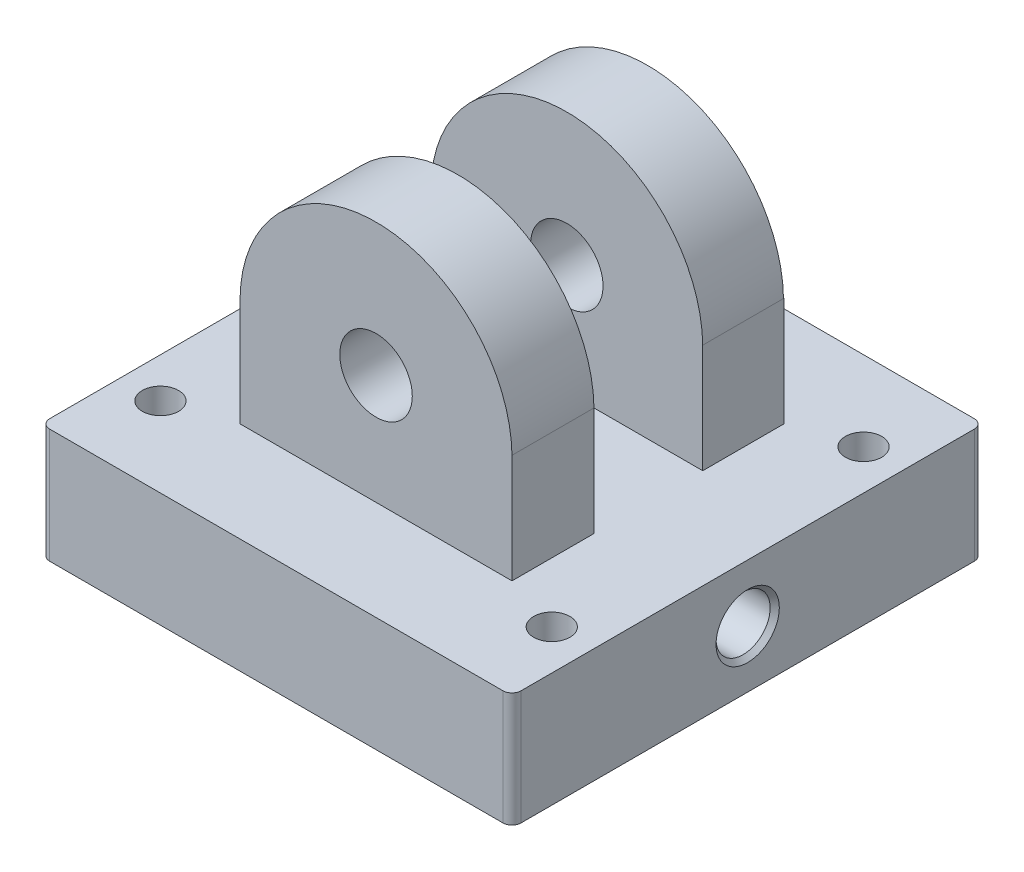
SolidWorks part; units mm, degrees
ref_plane "Front Plane" through (0, 0, 0) normal (0, 0, 1) x (1, 0, 0)
ref_plane "Top Plane" through (0, 0, 0) normal (0, 1, 0) x (1, 0, 0)
ref_plane "Right Plane" through (0, 0, 0) normal (1, 0, 0) x (0, 0, -1)
sketch "Sketch1" plane through (0, 0, 0) normal (0, 1, 0) x (1, 0, 0)
  line L1 (-82.55, 82.55) -> (82.55, 82.55)
  line L2 (-82.55, 82.55) -> (-82.55, -82.55)
  line L3 (-82.55, -82.55) -> (82.55, -82.55)
  line L4 (82.55, 82.55) -> (82.55, -82.55)
  line L5 (-82.55, 82.55) -> (82.55, -82.55) construction
  line L6 (-82.55, -82.55) -> (82.55, 82.55) construction
  point P0 (0, 0)
  dimension "D1" = 165.1
  dimension "D2" = 165.1
extrude "Boss-Extrude1" add sketch "Sketch1" along normal blind 38.1 and the other way blind 2
sketch "Sketch2" plane through (0, 38.1, 0) normal (0, 1, 0) x (1, 0, 0)
  line L1 (-47.625, 47.625) -> (47.625, 47.625)
  line L2 (-47.625, 47.625) -> (-47.625, -47.625)
  line L3 (-47.625, -47.625) -> (47.625, -47.625)
  line L4 (47.625, 47.625) -> (47.625, -47.625)
  line L5 (-47.625, 47.625) -> (47.625, -47.625) construction
  line L6 (-47.625, -47.625) -> (47.625, 47.625) construction
  point P0 (0, 0)
  dimension "D1" = 95.25
  dimension "D2" = 95.25
extrude "Boss-Extrude2" add sketch "Sketch2" along normal blind 38.1
sketch "Sketch4" plane through (0, 0, 47.625) normal (0, 0, 1) x (1, 0, 0)
  line L0 (-47.625, 76.2) -> (47.625, 76.2)
  arc A0 (-47.625, 76.2) -> (47.625, 76.2) centre (0, 75.5099) cw
  dimension "D1" = 47.63
extrude "Boss-Extrude5" add sketch "Sketch4" against normal blind 95.1
sketch "Sketch5" plane through (0, 0, 47.625) normal (0, 0, 1) x (1, 0, 0)
  circle A0 centre (0, 76.6438) radius 12.7
  dimension "D1" = 25.4
extrude "Cut-Extrude1" cut sketch "Sketch5" against normal through all
sketch "Sketch6" plane through (-47.625, 0, 0) normal (-1, 0, 0) x (0, 0, 1)
  line L0 (0, 0) -> (0, 127.301) construction
  line L1 (-47.625, 38.1) -> (47.625, 38.1) construction
  line L2 (-19.1913, 38.1) -> (18.9087, 38.1)
  line L3 (-19.1913, 38.1) -> (-19.1913, 123.1399)
  line L4 (-19.1913, 123.1399) -> (18.9087, 123.1399)
  line L5 (18.9087, 38.1) -> (18.9087, 123.1399)
  line L6 (47.625, 123.1399) -> (-47.475, 123.1399) construction
  dimension "D1" = 38.1
extrude "Cut-Extrude2" cut sketch "Sketch6" against normal through all
fillet "Fillet1" radius 3.175 4 edges at (82.55, 18.05, 82.55) (-82.55, 18.05, 82.55) (82.55, 18.05, -82.55) (-82.55, 18.05, -82.55)
sketch "Sketch7" plane through (0, -2, 0) normal (0, -1, 0) x (1, 0, 0)
  circle A0 centre (0, 0) radius 26
  dimension "D1" = 52
extrude "Cut-Extrude3" cut sketch "Sketch7" against normal blind 36.83
sketch "Sketch8" plane through (0, -2, 0) normal (0, -1, 0) x (1, 0, 0)
  circle A0 centre (0, 0) radius 69.85
  circle A1 centre (0, 0) radius 76.2
  dimension "D1" = 152.4
  dimension "D2" = 139.7
extrude "Cut-Extrude4" cut sketch "Sketch8" against normal blind 8
sketch "Sketch9" plane through (82.55, 0, 0) normal (1, 0, 0) x (0, 0, -1)
  line L0 (-79.375, 18.05) -> (79.375, 18.05) construction
  line L1 (-79.375, 38.1) -> (-79.375, -2) construction
  line L2 (79.375, -2) -> (79.375, 38.1) construction
sketch "Sketch12" plane through (82.55, 0, 0) normal (1, 0, 0) x (0, 0, -1)
  line L0 (79.375, 18.05) -> (-79.375, 18.05) construction
hole_wizard "1/2-14 NPSM Tapped Hole1" positions "Sketch13" profile "Sketch14" tap size "1/2-14 NPSM" standard "ANSI Inch"
sketch "Sketch13" plane through (82.55, 0, 0) normal (1, 0, 0) x (0, 0, -1)
  line L0 (-79.375, 18.05) -> (79.375, 18.05) construction
  point P0 (0, 18.05)
sketch "Sketch14" plane through (82.55, 18.05, 0) normal (0, 1, 0) x (0, 0, -1)
  line L0 (0, 0) -> (0, 69.2003)
  line L1 (0, 69.2003) -> (9.4869, 63.5)
  line L2 (9.4869, 63.5) -> (9.4869, 1.6002)
  line L3 (9.4869, 1.6002) -> (11.0871, 0)
  line L5 (11.0871, 0) -> (0, 0)
  line L6 (-9.4869, 1.6002) -> (-11.0871, 0) construction
  line L10 (0, 69.2003) -> (-9.4869, 63.5) construction
  line L11 (0, -6.35) -> (0, 107.95) construction
  dimension "Tap Drill Dia." = 18.9738
  dimension "Tap Drill Depth" = 63.5
  dimension "Near C'Sink Dia." = 22.1742
  dimension "Near C'Sink Angle" = 90
  dimension "Drill Angle" = 118
cosmetic thread "Hole Thread1" parameters "D1"=41.91, "D2"=20.9042
sketch "Sketch15" plane through (0, -2, 0) normal (0, -1, 0) x (1, 0, 0)
  line L0 (82.55, 79.375) -> (82.55, -79.375) construction
  circle A0 centre (50.3019, 0) radius 6.35
  dimension "D1" = 12.7
  dimension "D2" = 32.2481
extrude "Boss-Extrude6" add sketch "Sketch15" against normal blind 30
sketch "Sketch16" plane through (0, -2, 0) normal (0, -1, 0) x (1, 0, 0)
  line L0 (82.55, 79.375) -> (82.55, -79.375) construction
  circle A0 centre (50.55, 0) radius 6.35
  dimension "D1" = 12.7
  dimension "D2" = 32
extrude "Cut-Extrude5" cut sketch "Sketch16" against normal blind 25
sketch "Sketch17" plane through (0, -2, 0) normal (0, -1, 0) x (1, 0, 0)
  line L1 (-68.5386, 54.6029) -> (68.5386, 54.6029) construction
  line L2 (-68.5386, 54.6029) -> (-68.5386, -54.6029) construction
  line L3 (-68.5386, -54.6029) -> (68.5386, -54.6029) construction
  line L4 (68.5386, 54.6029) -> (68.5386, -54.6029) construction
  line L5 (-68.5386, 54.6029) -> (68.5386, -54.6029) construction
  line L6 (-68.5386, -54.6029) -> (68.5386, 54.6029) construction
  circle A0 centre (0, 0) radius 87.63 construction
  circle A1 centre (-68.5386, 54.6029) radius 6.35
  circle A2 centre (68.5386, 54.6029) radius 6.35
  circle A3 centre (-68.5386, -54.6029) radius 6.35
  circle A4 centre (68.5386, -54.6029) radius 6.35
  dimension "D1" = 175.26
  dimension "D2" = 12.7
  dimension "D3" = 12.7
  dimension "D4" = 12.7
  dimension "D5" = 12.7
extrude "Cut-Extrude6" cut sketch "Sketch17" against normal through all
